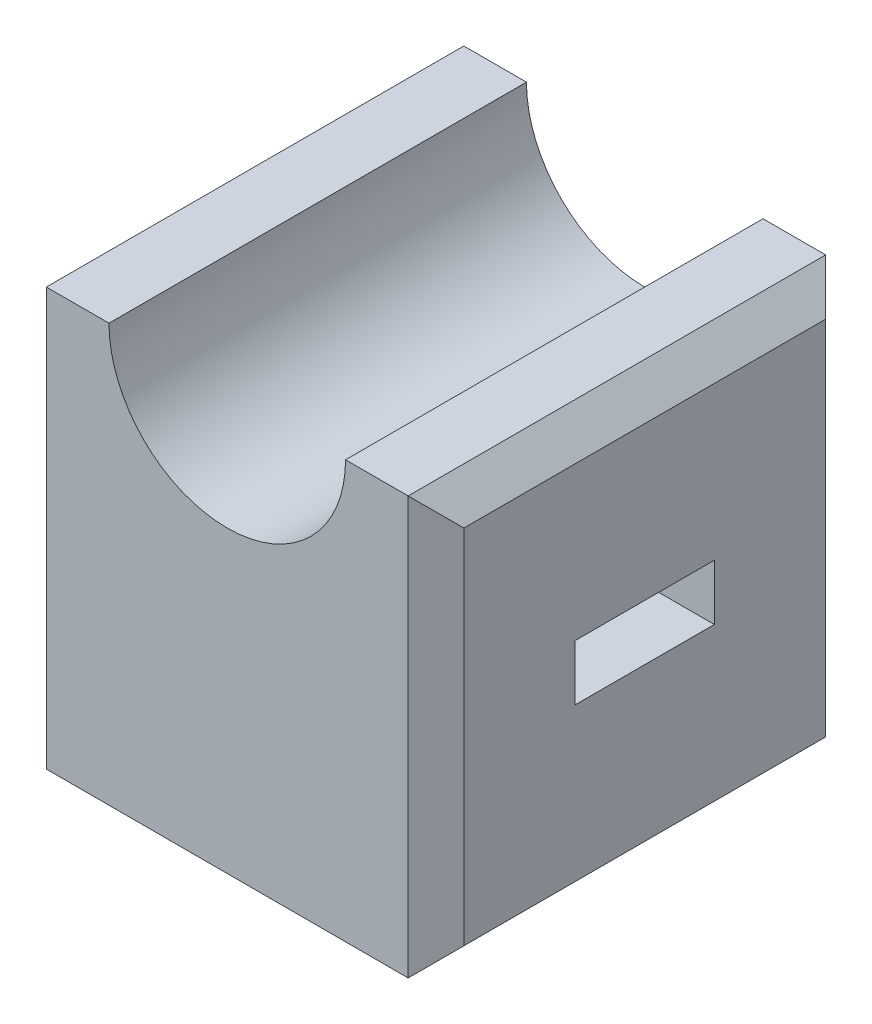
SolidWorks part; units mm, degrees
ref_plane "前视基准面" through (0, 0, 0) normal (0, 0, 1) x (1, 0, 0)
ref_plane "上视基准面" through (0, 0, 0) normal (0, 1, 0) x (1, 0, 0)
ref_plane "右视基准面" through (0, 0, 0) normal (1, 0, 0) x (0, 0, -1)
other "Configuration Table"
sketch "草图1" plane through (0, 0, 0) normal (0, 0, 1) x (1, 0, 0)
  line L0 (8.5, 15) -> (15, 15)
  line L1 (-15, -15) -> (15, -15)
  line L2 (-15, -15) -> (-15, 15)
  line L3 (-15, 15) -> (-8.5, 15)
  line L4 (15, -15) -> (15, 15)
  line L5 (-15, -15) -> (15, 15) construction
  line L6 (-15, 15) -> (15, -15) construction
  arc A0 (8.5, 15) -> (-8.5, 15) centre (0, 15) cw
  point P0 (0, 0)
  dimension "D1" = 30
  dimension "D2" = 30
extrude "凸台-拉伸1" add sketch "草图1" along normal blind 30
sketch "草图2" plane through (15, 0, 0) normal (1, 0, 0) x (0, 0, -1)
  line L0 (0, 0) -> (-30, 0) construction
  line L1 (-30, -15) -> (-30, 15) construction
  line L3 (-20, -2) -> (-10, -2)
  line L4 (-20, -2) -> (-20, 2)
  line L5 (-20, 2) -> (-10, 2)
  line L6 (-10, -2) -> (-10, 2)
  line L7 (-20, -2) -> (-10, 2) construction
  line L8 (-20, 2) -> (-10, -2) construction
  point P5 (-15, 0)
  dimension "D1" = 10
  dimension "D2" = 4
extrude "切除-拉伸1" cut sketch "草图2" against normal through all
chamfer "倒角1" distance 2 angle 45 2 edges at (15, 15, 15) (-15, 15, 15)
chamfer "倒角2" distance 2 angle 45 2 edges at (-15, -15, 15) (15, -15, 15)
chamfer "倒角3" distance 2 angle 45 4 edges at (-15, 0, 0) (-15, 0, 30) (15, 0, 30) (15, 0, 0)
